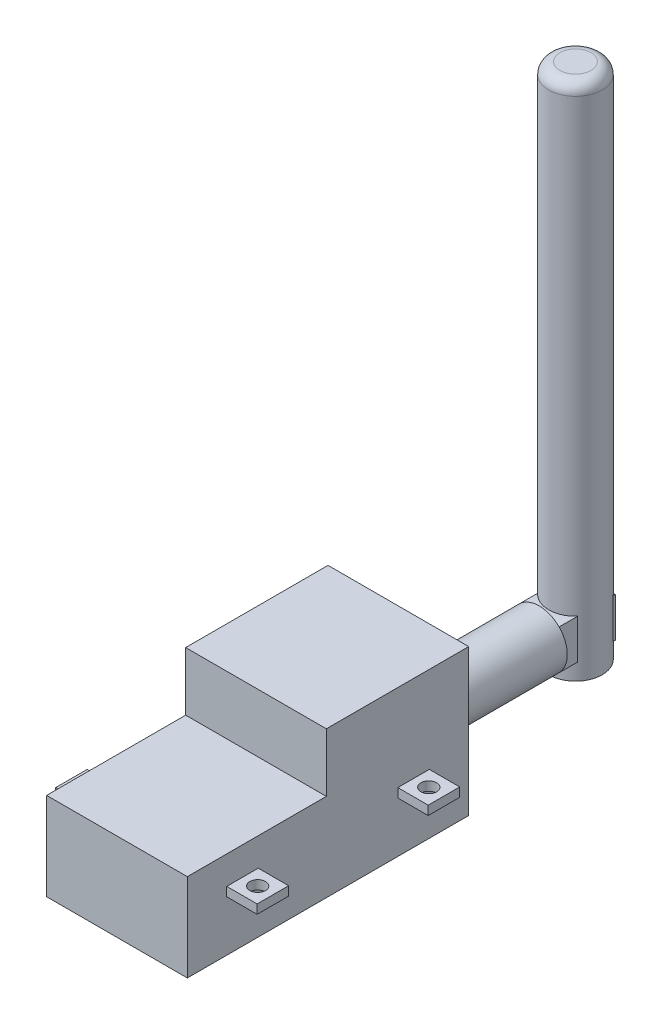
SolidWorks part; units mm, degrees
ref_plane "前视基准面" through (0, 0, 0) normal (0, 0, 1) x (1, 0, 0)
ref_plane "上视基准面" through (0, 0, 0) normal (0, 1, 0) x (1, 0, 0)
ref_plane "右视基准面" through (0, 0, 0) normal (1, 0, 0) x (0, 0, -1)
other "Configuration Table"
sketch "草图1" plane through (0, 0, 0) normal (0, 1, 0) x (1, 0, 0)
  line L0 (12.5, 25) -> (12.5, 18)
  line L1 (-12.5, -25) -> (12.5, -25)
  line L2 (-12.5, -25) -> (-12.5, 25)
  line L3 (-12.5, 25) -> (12.5, 25)
  line L4 (12.5, -25) -> (12.5, 25)
  line L5 (-12.5, -25) -> (12.5, 25) construction
  line L6 (-12.5, 25) -> (12.5, -25) construction
  line L7 (12.5, 18) -> (17.9, 18)
  line L8 (12.5, 18) -> (12.5, 12.4)
  line L9 (12.5, 12.4) -> (17.9, 12.4)
  line L10 (17.9, 18) -> (17.9, 12.4)
  line L11 (0, 25) -> (0, -25)
  line L12 (12.5, -12.4) -> (17.9, -12.4)
  line L13 (12.5, -12.4) -> (12.5, -18)
  line L14 (12.5, -18) -> (17.9, -18)
  line L15 (17.9, -12.4) -> (17.9, -18)
  line L16 (17.9, 12.4) -> (12.5, 18)
  line L17 (17.9, 18) -> (12.5, 12.4)
  line L18 (17.9, -12.4) -> (12.5, -18)
  line L19 (17.9, -18) -> (12.5, -12.4)
  line L20 (-12.5, -18) -> (-17.9, -18)
  line L21 (-17.9, -12.4) -> (-17.9, -18)
  line L22 (-12.5, -12.4) -> (-17.9, -12.4)
  line L23 (-12.5, -12.4) -> (-12.5, -18)
  line L24 (-12.5, 12.4) -> (-17.9, 12.4)
  line L25 (-17.9, 18) -> (-17.9, 12.4)
  line L26 (-12.5, 18) -> (-17.9, 18)
  line L27 (-12.5, 18) -> (-12.5, 12.4)
  circle A0 centre (15.2, 15.2) radius 1.4
  circle A1 centre (15.2, -15.2) radius 1.4
  circle A2 centre (-15.2, -15.2) radius 1.4
  circle A3 centre (-15.2, 15.2) radius 1.4
  point P0 (0, 0)
  dimension "D8" = 2.8
  dimension "D9" = 2.8
  dimension "D1" = 25
  dimension "D2" = 50
  dimension "D3" = 5.6
  dimension "D4" = 5.4
  dimension "D5" = 7
  dimension "D6" = 5.6
  dimension "D7" = 7
extrude "凸台-拉伸1" add sketch "草图1" along normal blind 1.6 contours L11 L3 L2 L1 | L3 L11 L1 L4 L0 | L2 L22 L21 L20 A2 | L2 L26 L25 L24 A3 | A0 L17 L9 L16 | A0 L17 L7 L16 | A0 L16 L10 L17 | A0 L16 L4 L17 | A1 L18 L12 L19 | A1 L19 L4 L18 | A1 L19 L15 L18 | A1 L18 L14 L19
sketch "草图3" plane through (0, 1.6, 0) normal (0, 1, 0) x (1, 0, 0)
  line L1 (-12.5, 25) -> (12.5, 25)
  line L2 (-12.5, 25) -> (-12.5, -25)
  line L3 (-12.5, -25) -> (12.5, -25)
  line L4 (12.5, 25) -> (12.5, -25)
  line L20 (-12.5, -25) -> (12.5, -25)
  line L21 (12.5, -25) -> (12.5, -18)
  line L22 (12.5, -18) -> (17.9, -18)
  line L23 (17.9, -18) -> (17.9, -12.4)
  line L24 (17.9, -12.4) -> (12.5, -12.4)
  line L25 (12.5, -12.4) -> (12.5, 12.4)
  line L26 (12.5, 12.4) -> (17.9, 12.4)
  line L27 (17.9, 12.4) -> (17.9, 18)
  line L28 (17.9, 18) -> (12.5, 18)
  line L29 (12.5, 18) -> (12.5, 25)
  line L30 (12.5, 25) -> (-12.5, 25)
  line L31 (-12.5, 25) -> (-12.5, 18)
  line L32 (-12.5, 18) -> (-17.9, 18)
  line L33 (-17.9, 18) -> (-17.9, 12.4)
  line L34 (-17.9, 12.4) -> (-12.5, 12.4)
  line L35 (-12.5, 12.4) -> (-12.5, -12.4)
  line L36 (-12.5, -12.4) -> (-17.9, -12.4)
  line L37 (-17.9, -12.4) -> (-17.9, -18)
  line L38 (-17.9, -18) -> (-12.5, -18)
  line L39 (-12.5, -18) -> (-12.5, -25)
  line L40 (-12.5, -25) -> (12.5, -25)
  line L41 (12.5, -25) -> (12.5, -18)
  line L42 (12.5, -18) -> (17.9, -18)
  line L43 (17.9, -18) -> (17.9, -12.4)
  line L44 (17.9, -12.4) -> (12.5, -12.4)
  line L45 (12.5, -12.4) -> (12.5, 12.4)
  line L46 (12.5, 12.4) -> (17.9, 12.4)
  line L47 (17.9, 12.4) -> (17.9, 18)
  line L48 (17.9, 18) -> (12.5, 18)
  line L49 (12.5, 18) -> (12.5, 25)
  line L50 (12.5, 25) -> (-12.5, 25)
  line L51 (-12.5, 25) -> (-12.5, 18)
  line L52 (-12.5, 18) -> (-17.9, 18)
  line L53 (-17.9, 18) -> (-17.9, 12.4)
  line L54 (-17.9, 12.4) -> (-12.5, 12.4)
  line L55 (-12.5, 12.4) -> (-12.5, -12.4)
  line L56 (-12.5, -12.4) -> (-17.9, -12.4)
  line L57 (-17.9, -12.4) -> (-17.9, -18)
  line L58 (-17.9, -18) -> (-12.5, -18)
  line L59 (-12.5, -18) -> (-12.5, -25)
  line M23 (-12.5, -25) -> (12.5, -25)
  line M24 (12.5, -25) -> (12.5, -18)
  line M28 (12.5, -12.4) -> (12.5, 12.4)
  line M32 (12.5, 18) -> (12.5, 25)
  line M33 (12.5, 25) -> (-12.5, 25)
  line M34 (-12.5, 25) -> (-12.5, 18)
  line M38 (-12.5, 12.4) -> (-12.5, -12.4)
  line M42 (-12.5, -18) -> (-12.5, -25)
  dimension "D1" = 0
extrude "凸台-拉伸2" add sketch "草图3" along normal blind 5 contours L4 L2 M32 M33 M34 M38 M42 M23 M24 M28
sketch "草图4" plane through (0, 0, 0) normal (0, -1, 0) x (1, 0, 0)
  line L1 (-12.5, 25) -> (12.5, 25)
  line L2 (-12.5, 25) -> (-12.5, -25)
  line L3 (-12.5, -25) -> (12.5, -25)
  line L4 (12.5, 25) -> (12.5, -25)
  line L20 (12.5, 25) -> (-12.5, 25)
  line L21 (-12.5, 25) -> (-12.5, 18)
  line L22 (-12.5, 18) -> (-17.9, 18)
  line L23 (-17.9, 18) -> (-17.9, 12.4)
  line L24 (-17.9, 12.4) -> (-12.5, 12.4)
  line L25 (-12.5, 12.4) -> (-12.5, -12.4)
  line L26 (-12.5, -12.4) -> (-17.9, -12.4)
  line L27 (-17.9, -12.4) -> (-17.9, -18)
  line L28 (-17.9, -18) -> (-12.5, -18)
  line L29 (-12.5, -18) -> (-12.5, -25)
  line L30 (-12.5, -25) -> (12.5, -25)
  line L31 (12.5, -25) -> (12.5, -18)
  line L32 (12.5, -18) -> (17.9, -18)
  line L33 (17.9, -18) -> (17.9, -12.4)
  line L34 (17.9, -12.4) -> (12.5, -12.4)
  line L35 (12.5, -12.4) -> (12.5, 12.4)
  line L36 (12.5, 12.4) -> (17.9, 12.4)
  line L37 (17.9, 12.4) -> (17.9, 18)
  line L38 (17.9, 18) -> (12.5, 18)
  line L39 (12.5, 18) -> (12.5, 25)
  line L40 (12.5, 25) -> (-12.5, 25)
  line L41 (-12.5, 25) -> (-12.5, 18)
  line L42 (-12.5, 18) -> (-17.9, 18)
  line L43 (-17.9, 18) -> (-17.9, 12.4)
  line L44 (-17.9, 12.4) -> (-12.5, 12.4)
  line L45 (-12.5, 12.4) -> (-12.5, -12.4)
  line L46 (-12.5, -12.4) -> (-17.9, -12.4)
  line L47 (-17.9, -12.4) -> (-17.9, -18)
  line L48 (-17.9, -18) -> (-12.5, -18)
  line L49 (-12.5, -18) -> (-12.5, -25)
  line L50 (-12.5, -25) -> (12.5, -25)
  line L51 (12.5, -25) -> (12.5, -18)
  line L52 (12.5, -18) -> (17.9, -18)
  line L53 (17.9, -18) -> (17.9, -12.4)
  line L54 (17.9, -12.4) -> (12.5, -12.4)
  line L55 (12.5, -12.4) -> (12.5, 12.4)
  line L56 (12.5, 12.4) -> (17.9, 12.4)
  line L57 (17.9, 12.4) -> (17.9, 18)
  line L58 (17.9, 18) -> (12.5, 18)
  line L59 (12.5, 18) -> (12.5, 25)
  line M23 (12.5, 25) -> (-12.5, 25)
  line M24 (-12.5, 25) -> (-12.5, 18)
  line M28 (-12.5, 12.4) -> (-12.5, -12.4)
  line M32 (-12.5, -18) -> (-12.5, -25)
  line M33 (-12.5, -25) -> (12.5, -25)
  line M34 (12.5, -25) -> (12.5, -18)
  line M38 (12.5, -12.4) -> (12.5, 12.4)
  line M42 (12.5, 18) -> (12.5, 25)
  dimension "D1" = 0
extrude "凸台-拉伸3" add sketch "草图4" along normal blind 9 contours L4 L2 M42 M23 M24 M28 M32 M33 M34 M38
sketch "草图5" plane through (0, 6.6, 0) normal (0, 1, 0) x (1, 0, 0)
  line L1 (-12.5, 25) -> (12.5, 25)
  line L2 (-12.5, 25) -> (-12.5, -0.3)
  line L3 (-12.5, -0.3) -> (12.5, -0.3)
  line L4 (12.5, -25) -> (12.5, 25)
  line L5 (12.5, 25) -> (-12.5, 25)
  line L6 (-12.5, 25) -> (-12.5, -25)
  line L7 (-12.5, -25) -> (12.5, -25)
  line L8 (12.5, -25) -> (12.5, 25)
  line L9 (12.5, 25) -> (-12.5, 25)
  line L10 (-12.5, 25) -> (-12.5, -25)
  line L11 (-12.5, -25) -> (12.5, -25)
  line L12 (12.5, 25) -> (12.5, -0.3)
  line M5 (12.5, -25) -> (12.5, 25)
  line M6 (12.5, 25) -> (-12.5, 25)
  line M7 (-12.5, 25) -> (-12.5, -25)
  dimension "D2" = 25.3
  dimension "D1" = 0
extrude "凸台-拉伸4" add sketch "草图5" along normal blind 10.4 contours L3 M7 M5 M6
sketch "草图6" plane through (0, 0, -25) normal (0, 0, -1) x (-1, 0, 0)
  line L0 (0, -9) -> (0, -3.15)
  line L1 (0, -3.15) -> (0, 2.18)
  line L2 (0, 2.18) -> (0, -3.15) construction
  line L4 (-12.5, 17) -> (-12.5, -9)
  line L5 (-12.5, -9) -> (12.5, -9)
  line L6 (12.5, -9) -> (12.5, 17)
  line L7 (12.5, 17) -> (-12.5, 17)
  line L8 (-12.5, 17) -> (-12.5, -9)
  line L9 (-12.5, -9) -> (12.5, -9)
  line L10 (12.5, -9) -> (12.5, 17)
  line L11 (12.5, 17) -> (-12.5, 17)
  circle A0 centre (0, -0.485) radius 2.665
  dimension "D2" = 5.85
  dimension "D3" = 5.33
  dimension "D1" = 0
extrude "凸台-拉伸5" add sketch "草图6" along normal blind 4.43 contours L1 A0 | L1 A0
sketch "草图7" plane through (0, 0, -29.43) normal (0, 0, -1) x (-1, 0, 0)
  circle A0 centre (0, -0.485) radius 5
  dimension "D2" = 10
extrude "凸台-拉伸6" add sketch "草图7" along normal blind 20.58
sketch "草图8" plane through (0, 0, -50.01) normal (0, 0, -1) x (-1, 0, 0)
  line L1 (-3.5438, -4.0122) -> (3.5438, -4.0122)
  line L2 (-3.5438, -4.0122) -> (-3.5438, 3.0422)
  line L3 (-3.5438, 3.0422) -> (3.5438, 3.0422)
  line L4 (3.5438, -4.0122) -> (3.5438, 3.0422)
  line L5 (-3.5438, -4.0122) -> (3.5438, 3.0422) construction
  line L6 (-3.5438, 3.0422) -> (3.5438, -4.0122) construction
  circle A1 centre (0, -0.485) radius 5
  circle A2 centre (0, -0.485) radius 5
  dimension "D1" = 0
extrude "凸台-拉伸7" add sketch "草图8" along normal blind 10 contours L1 L4 L3 L2
sketch "草图9" plane through (0, 3.0422, 0) normal (0, 1, 0) x (1, 0, 0)
  line L0 (-3.5438, 60.01) -> (3.5438, 52.92)
  line L1 (-3.5438, 60.01) -> (3.5438, 60.01)
  line L2 (-3.5438, 60.01) -> (-3.5438, 52.92)
  line L3 (-3.5438, 52.92) -> (3.5438, 52.92)
  line L4 (-3.5438, 50.01) -> (3.5438, 50.01)
  line L5 (3.5438, 50.01) -> (3.5438, 60.01)
  line L6 (3.5438, 60.01) -> (-3.5438, 60.01)
  line L7 (-3.5438, 60.01) -> (-3.5438, 50.01)
  line L8 (-3.5438, 50.01) -> (3.5438, 50.01)
  line L9 (3.5438, 50.01) -> (3.5438, 60.01)
  line L10 (3.5438, 60.01) -> (-3.5438, 60.01)
  line L11 (-3.5438, 60.01) -> (-3.5438, 50.01)
  line L12 (3.5438, 60.01) -> (3.5438, 52.92)
  line L13 (3.5438, 60.01) -> (-3.5438, 52.92)
  circle A0 centre (0, 56.465) radius 4.75
  dimension "D3" = 9.5
  dimension "D2" = 7.09
  dimension "D1" = 0
extrude "凸台-拉伸8" add sketch "草图9" along normal blind 82 and the other way blind 10 contours L12 A0 | L10 A0 | L11 A0 | L3 A0 | L3 A0 L0 L13 | L0 A0 L11 L13 | L13 A0 L10 L0 | L0 A0 L12 L13
fillet "圆角1" radius 2 1 edges at (0, 85.0422, -51.715)
